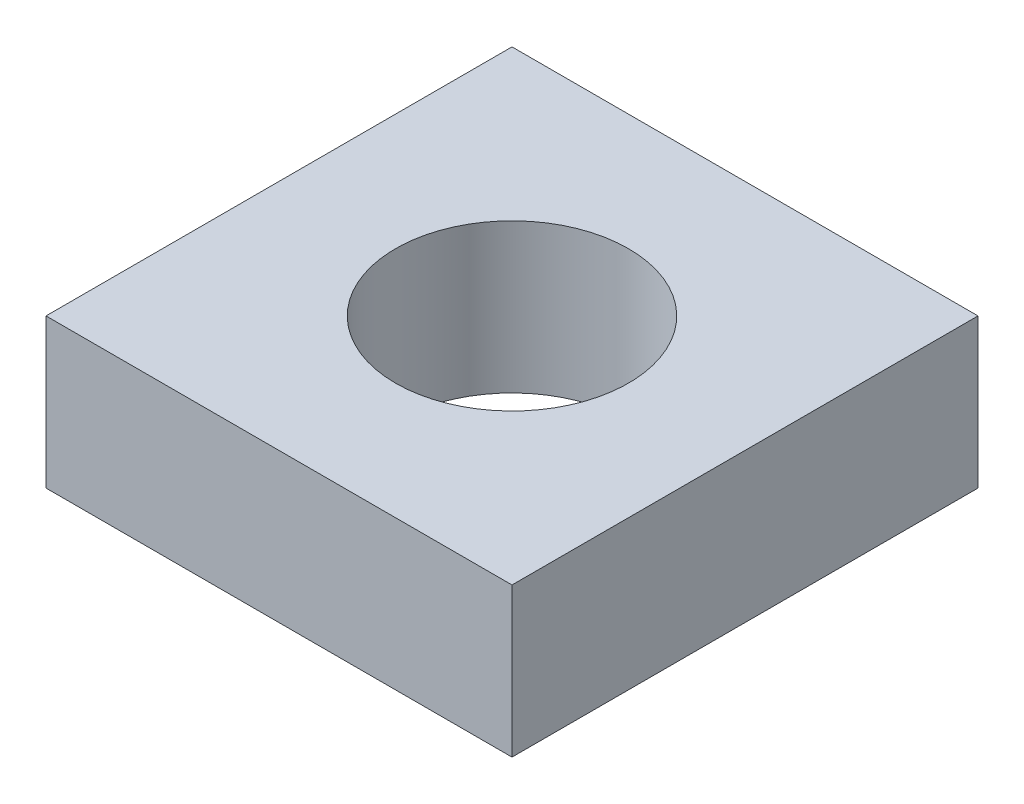
SolidWorks part; units mm, degrees
ref_plane "Přední rovina" through (0, 0, 0) normal (0, 0, 1) x (1, 0, 0)
ref_plane "Horní rovina" through (0, 0, 0) normal (0, 1, 0) x (1, 0, 0)
ref_plane "Pravá rovina" through (0, 0, 0) normal (1, 0, 0) x (0, 0, -1)
sketch "Skica1" plane through (0, 0, 0) normal (0, 1, 0) x (1, 0, 0)
  line L1 (2.5, -2.5) -> (-2.5, -2.5)
  line L2 (2.5, -2.5) -> (2.5, 2.5)
  line L3 (2.5, 2.5) -> (-2.5, 2.5)
  line L4 (-2.5, -2.5) -> (-2.5, 2.5)
  line L5 (2.5, -2.5) -> (-2.5, 2.5) construction
  line L6 (2.5, 2.5) -> (-2.5, -2.5) construction
  circle A0 centre (0, 0) radius 1.25
  point P0 (0, 0)
  dimension "D3" = 2.5
  dimension "D1" = 5
  dimension "D2" = 5
extrude "Přidat vysunutím1" add sketch "Skica1" along normal blind 1.6
